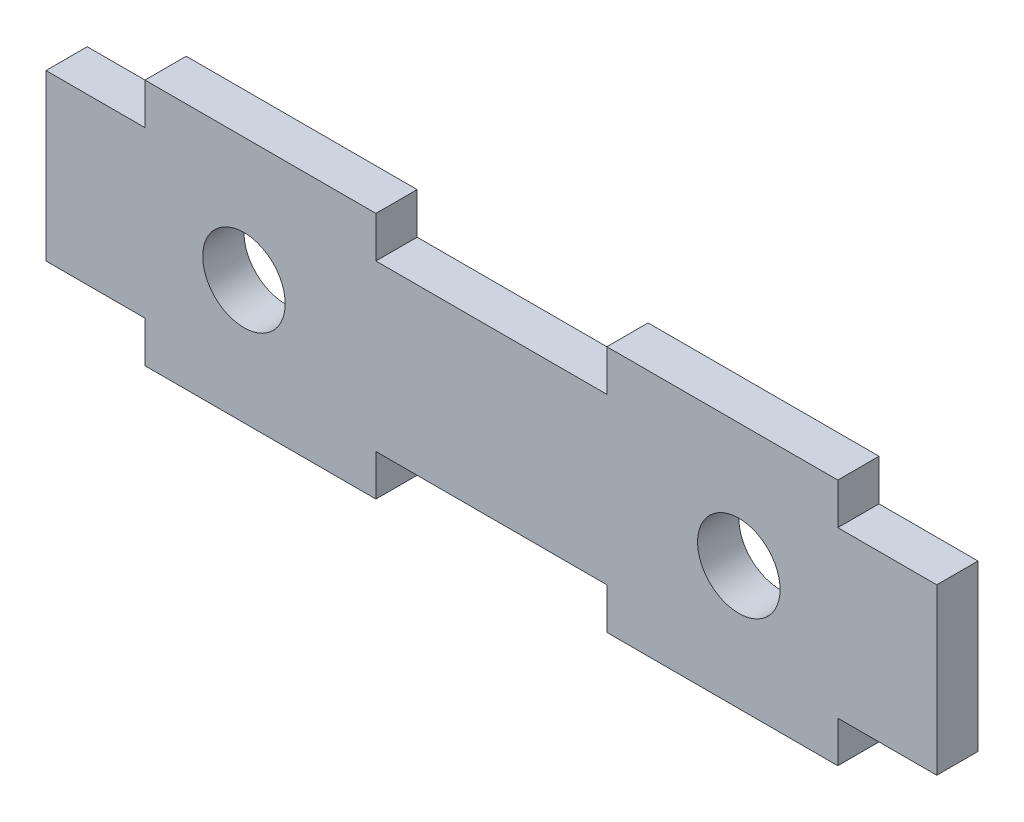
SolidWorks part; units mm, degrees
material "Oak"
ref_plane "Front Plane" through (0, 0, 0) normal (0, 0, 1) x (1, 0, 0)
ref_plane "Top Plane" through (0, 0, 0) normal (0, 1, 0) x (1, 0, 0)
ref_plane "Right Plane" through (0, 0, 0) normal (1, 0, 0) x (0, 0, -1)
sketch "Sketch1" plane through (0, 0, 0) normal (0, 0, 1) x (1, 0, 0)
  line L1 (0, 0) -> (76.2, 0)
  line L2 (0, 0) -> (0, -19.05)
  line L3 (0, -19.05) -> (76.2, -19.05)
  line L4 (76.2, 0) -> (76.2, -19.05)
extrude "Boss-Extrude1" add sketch "Sketch1" along normal blind 3.175
sketch "Sketch2" plane through (0, 0, 3.175) normal (0, 0, 1) x (1, 0, 0)
  line L1 (0, 0) -> (11.43, 0)
  line L2 (0, 0) -> (0, -3.175)
  line L3 (0, -3.175) -> (11.43, -3.175)
  line L4 (11.43, 0) -> (11.43, -3.175)
extrude "Cut-Extrude1" cut sketch "Sketch2" against normal through all
ref_plane "Plane1" through (0, -9.525, 0) normal (0, 1, 0) x (1, 0, 0)
ref_plane "Plane2" through (38.1, 0, 0) normal (1, 0, 0) x (0, 0, -1)
mirror "Mirror1" about plane through (38.1, 0, 0) normal (1, 0, 0) of "Cut-Extrude1"
sketch "Sketch3" plane through (0, 0, 3.175) normal (0, 0, 1) x (1, 0, 0)
  line L0 (64.77, 0) -> (11.43, 0) construction
  line L1 (29.21, -3.175) -> (46.99, -3.175)
  line L2 (29.21, -3.175) -> (29.21, 0)
  line L3 (29.21, 0) -> (46.99, 0)
  line L4 (46.99, -3.175) -> (46.99, 0)
extrude "Cut-Extrude2" cut sketch "Sketch3" against normal through all
mirror "Mirror2" about plane through (0, -9.525, 0) normal (0, 1, 0) of "Cut-Extrude1", "Mirror1", "Cut-Extrude2"
hole_wizard "Hole1" positions "Sketch5" profile "Sketch4" legacy end condition through all
sketch "Sketch5" plane through (0, 0, 3.175) normal (0, 0, 1) x (1, 0, 0)
  line L0 (1.397, -9.525) -> (-1.397, -9.525) construction
  point P0 (19.05, -9.525)
  point P4 (57.15, -9.525)
sketch "Sketch4" plane through (19.05, -9.525, 3.175) normal (1, 0, 0) x (0, -1, 0)
  line L0 (0, 0) -> (0, 3.175)
  line L1 (0, 3.175) -> (3.175, 3.175)
  line L2 (3.175, 3.175) -> (3.175, 0)
  line L3 (3.175, 0) -> (0, 0)
  line L4 (0, 110) -> (0, -10) construction
  dimension "Diameter" = 6.35
  dimension "Depth" = 3.175
sketch "Sketch6" plane through (0, 0, 0) normal (-1, 0, 0) x (0, 0, 1)
  line L1 (0, -3.175) -> (3.175, -3.175)
  line L2 (0, -3.175) -> (0, -15.875)
  line L3 (0, -15.875) -> (3.175, -15.875)
  line L4 (3.175, -3.175) -> (3.175, -15.875)
extrude "Cut-Extrude3" cut sketch "Sketch6" against normal blind 3.81
sketch "Sketch7" plane through (76.2, 0, 0) normal (1, 0, 0) x (0, 0, -1)
  line L1 (0, -3.175) -> (-3.175, -3.175)
  line L2 (0, -3.175) -> (0, -15.875)
  line L3 (0, -15.875) -> (-3.175, -15.875)
  line L4 (-3.175, -3.175) -> (-3.175, -15.875)
extrude "Cut-Extrude4" cut sketch "Sketch7" against normal blind 3.81
